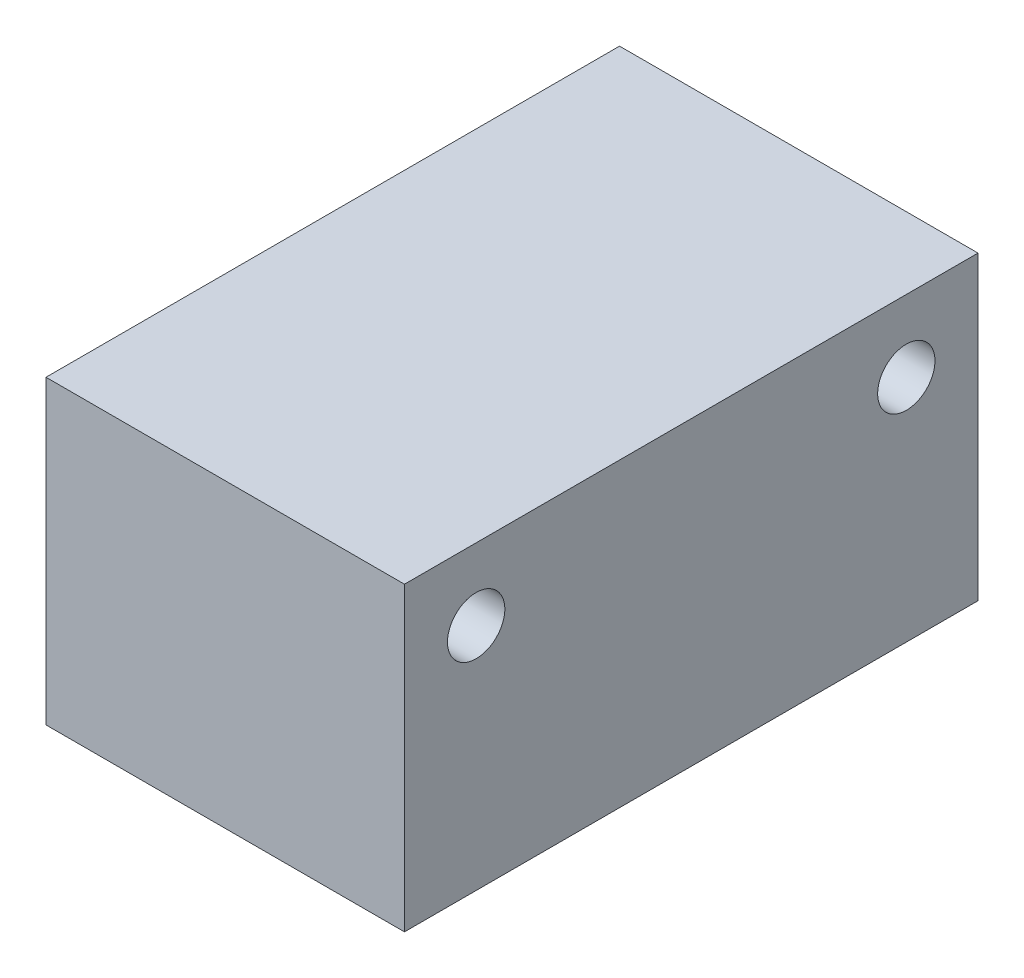
SolidWorks part; units mm, degrees
ref_plane "Front Plane" through (0, 0, 0) normal (0, 0, 1) x (1, 0, 0)
ref_plane "Top Plane" through (0, 0, 0) normal (0, 1, 0) x (1, 0, 0)
ref_plane "Right Plane" through (0, 0, 0) normal (1, 0, 0) x (0, 0, -1)
sketch "Sketch1" plane through (0, 0, 0) normal (0, 1, 0) x (1, 0, 0)
  line L1 (-25, -40) -> (25, -40)
  line L2 (-25, -40) -> (-25, 40)
  line L3 (-25, 40) -> (25, 40)
  line L4 (25, -40) -> (25, 40)
  line L5 (-25, -40) -> (25, 40) construction
  line L6 (-25, 40) -> (25, -40) construction
  point P0 (0, 0)
  dimension "D1" = 50
  dimension "D2" = 80
extrude "Boss-Extrude1" add sketch "Sketch1" along normal blind 42
sketch "Sketch2" plane through (0, 0, 0) normal (0, -1, 0) x (1, 0, 0)
  line L1 (-17.5, -22.5) -> (17.5, -22.5)
  line L2 (-17.5, -22.5) -> (-17.5, 22.5)
  line L3 (-17.5, 22.5) -> (17.5, 22.5)
  line L4 (17.5, -22.5) -> (17.5, 22.5)
  line L5 (-17.5, -22.5) -> (17.5, 22.5) construction
  line L6 (-17.5, 22.5) -> (17.5, -22.5) construction
  point P0 (0, 0)
  dimension "D1" = 45
  dimension "D2" = 35
extrude "Boss-Extrude2" add sketch "Sketch2" along normal blind 5
sketch "Sketch3" plane through (-25, 0, 0) normal (-1, 0, 0) x (0, 0, 1)
  line L0 (-40, 42) -> (40, 42) construction
  line L2 (40, 42) -> (40, 0) construction
  line L3 (-40, 42) -> (-40, 0) construction
  circle A0 centre (-30, 32) radius 4
  circle A1 centre (30, 32) radius 4
  dimension "D1" = 8
  dimension "D2" = 8
  dimension "D3" = 10
  dimension "D4" = 10
  dimension "D5" = 10
  dimension "D6" = 10
extrude "Cut-Extrude1" cut sketch "Sketch3" against normal through all
